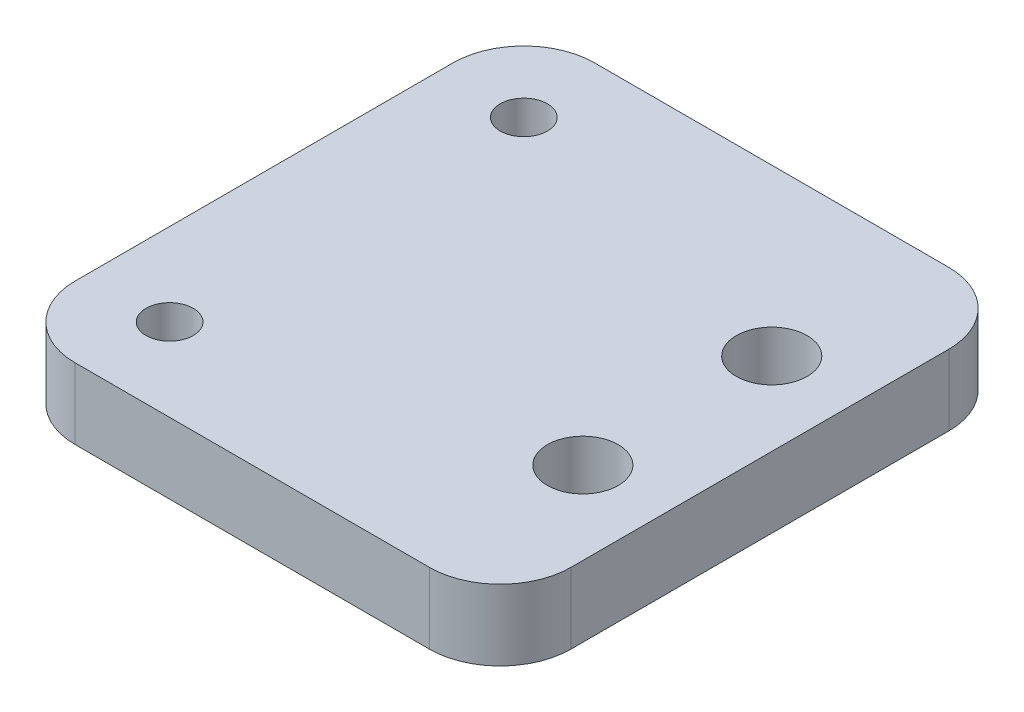
SolidWorks part; units mm, degrees
material "Thornel Mat VMA"
ref_plane "前视基准面" through (0, 0, 0) normal (0, 0, 1) x (1, 0, 0)
ref_plane "上视基准面" through (0, 0, 0) normal (0, 1, 0) x (1, 0, 0)
ref_plane "右视基准面" through (0, 0, 0) normal (1, 0, 0) x (0, 0, -1)
other "Configuration Table"
sketch "草图1" plane through (0, 0, 0) normal (0, 1, 0) x (1, 0, 0)
  line L0 (3.5, 11) -> (17.5, 11)
  line L1 (-3.5, -11) -> (3.5, -11)
  line L2 (-3.5, -11) -> (-3.5, 11)
  line L3 (-3.5, 11) -> (3.5, 11)
  line L4 (3.5, -11) -> (3.5, 11)
  line L5 (-3.5, -11) -> (3.5, 11) construction
  line L6 (-3.5, 11) -> (3.5, -11) construction
  line L7 (17.5, 11) -> (17.5, -11)
  line L8 (17.5, -11) -> (3.5, -11)
  circle A0 centre (0, 7.5) radius 1
  circle A1 centre (0, -7.5) radius 1
  circle A2 centre (14, 4) radius 1.5
  circle A3 centre (14, -4) radius 1.5
  point P0 (0, 0)
  dimension "D3" = 2
  dimension "D4" = 2
  dimension "D5" = 15
  dimension "D6" = 7.5
  dimension "D8" = 3.5
  dimension "D10" = 3
  dimension "D11" = 3
  dimension "D12" = 8
  dimension "D13" = 7
  dimension "D14" = 10.5
  dimension "D15" = 10.5
  dimension "D1" = 7
  dimension "D2" = 22
  dimension "D7" = 3.5
  dimension "D9" = 14
extrude "凸台-拉伸1" add sketch "草图1" along normal blind 3 contours L1 L4 L3 L2 A1 A0 | L8 L7 L0 L4 A3 A2
fillet "圆角1" radius 3 4 edges at (-3.5, 1.5, -11) (-3.5, 1.5, 11) (17.5, 1.5, -11) (17.5, 1.5, 11)
